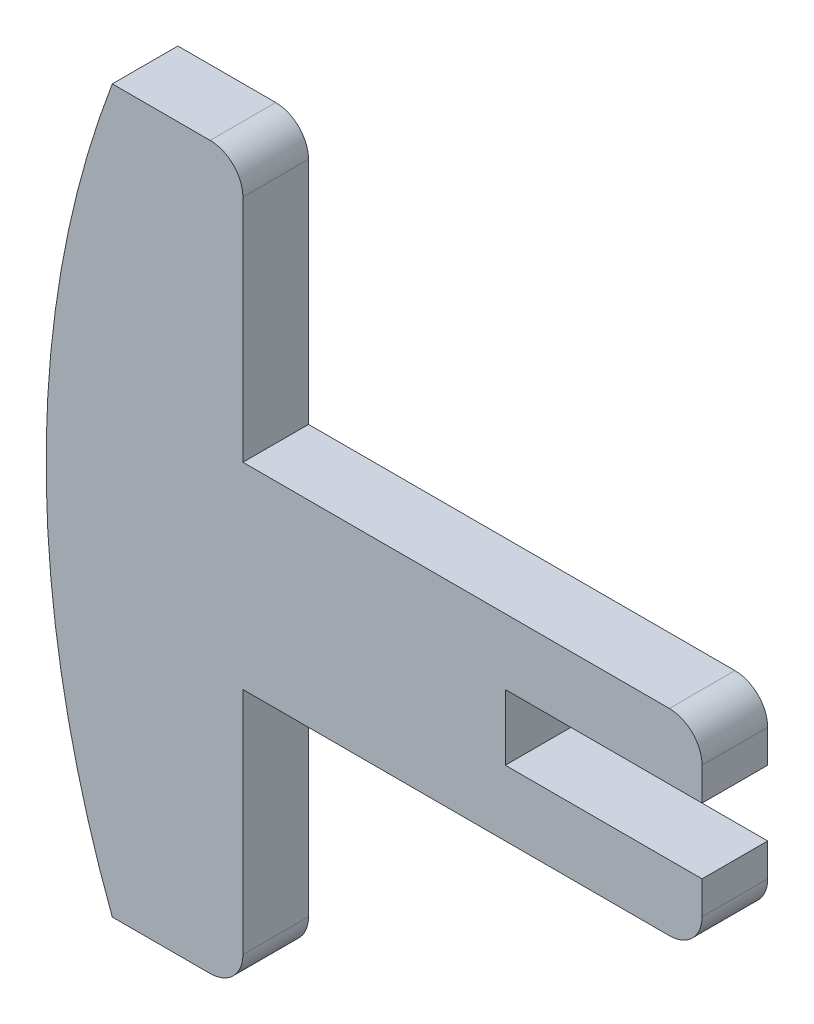
SolidWorks part; units mm, degrees
ref_plane "Front Plane" through (0, 0, 0) normal (0, 0, 1) x (1, 0, 0)
ref_plane "Top Plane" through (0, 0, 0) normal (0, 1, 0) x (1, 0, 0)
ref_plane "Right Plane" through (0, 0, 0) normal (1, 0, 0) x (0, 0, -1)
sketch "Sketch1" plane through (0, 0, 0) normal (0, 0, 1) x (1, 0, 0)
  line L0 (-25, 3) -> (-12, 3)
  line L1 (-25, -3) -> (-12, -3)
  line L2 (-28.9828, 11) -> (-26, 11)
  line L3 (-25, 10) -> (-25, 3)
  line L4 (-28.9828, -11) -> (-26, -11)
  line L5 (-25, -3) -> (-25, -10)
  line L6 (-17, 1) -> (-17, -1)
  line L7 (-17, 1) -> (-11, 1)
  line L8 (-17, -1) -> (-11, -1)
  line L9 (-11, 1) -> (-11, 2)
  line L10 (-11, -1) -> (-11, -2)
  arc A0 (-28.9828, 11) -> (-28.9828, -11) centre (0, 0) ccw
  arc A1 (-25, 10) -> (-26, 11) centre (-26, 10) ccw
  arc A2 (-25, -10) -> (-26, -11) centre (-26, -10) cw
  arc A3 (-11, -2) -> (-12, -3) centre (-12, -2) cw
  arc A4 (-11, 2) -> (-12, 3) centre (-12, 2) ccw
  dimension "D1" = 8
  dimension "D6" = 31
  dimension "D5" = 1
  dimension "D2" = 8
  dimension "D3" = 3
  dimension "D4" = 25
  dimension "D7" = 17
  dimension "D8" = 2
  dimension "D9" = 1
  dimension "D10" = 6
extrude "Boss-Extrude1" add sketch "Sketch1" along normal blind 2
